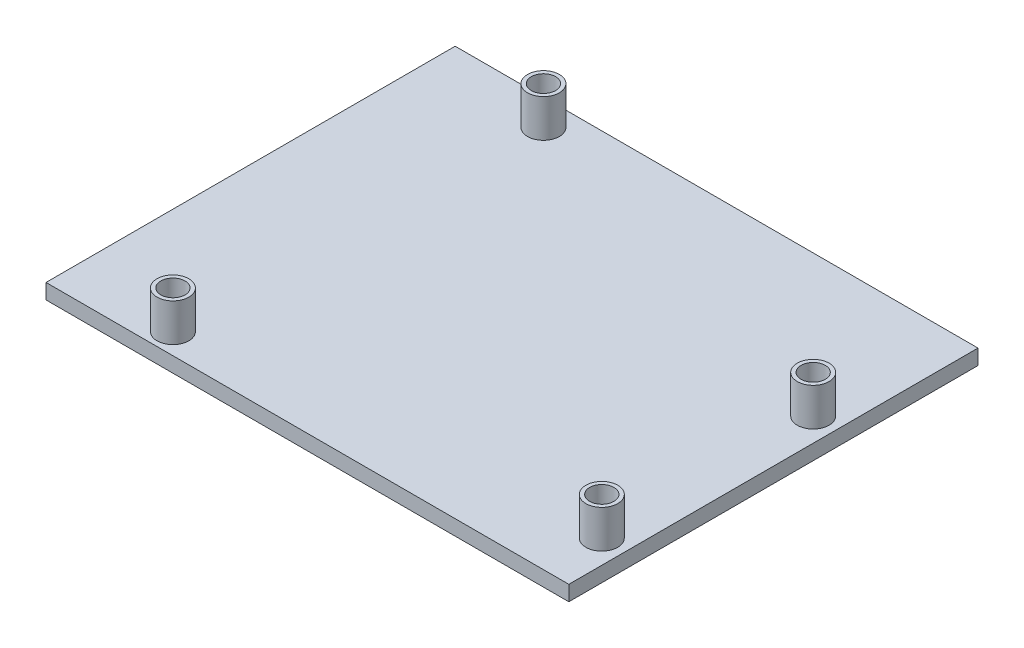
SolidWorks part; units mm, degrees
ref_plane "Front" through (0, 0, 0) normal (0, 0, 1) x (1, 0, 0)
ref_plane "Top" through (0, 0, 0) normal (0, 1, 0) x (1, 0, 0)
ref_plane "Right" through (0, 0, 0) normal (1, 0, 0) x (0, 0, -1)
sketch "Sketch1" plane through (0, 0, 0) normal (0, 1, 0) x (1, 0, 0)
  line L1 (-34.5, -27) -> (34.5, -27)
  line L2 (-34.5, -27) -> (-34.5, 27)
  line L3 (-34.5, 27) -> (34.5, 27)
  line L4 (34.5, -27) -> (34.5, 27)
  line L5 (-34.5, -27) -> (34.5, 27) construction
  line L6 (-34.5, 27) -> (34.5, -27) construction
  point P0 (0, 0)
  dimension "D1" = 69
  dimension "D2" = 54
extrude "Boss-Extrude1" add sketch "Sketch1" along normal blind 2
sketch "Sketch2" plane through (0, 2, 0) normal (0, 1, 0) x (1, 0, 0)
  line L0 (-34.5, -27) -> (34.5, -27) construction
  line L1 (-34.5, 27) -> (-34.5, -27) construction
  circle A0 centre (-20.5, -24.25) radius 1.6
  circle A1 centre (31.4, -19.55) radius 1.6
  circle A2 centre (31.4, 8.35) radius 1.6
  circle A3 centre (-19.4, 23.55) radius 1.6
  circle A4 centre (-19.4, 23.55) radius 2.1
  circle A5 centre (31.4, 8.35) radius 2.1
  circle A6 centre (31.4, -19.55) radius 2.1
  circle A7 centre (-20.5, -24.25) radius 2.1
  dimension "D1" = 3.2
  dimension "D2" = 14
  dimension "D3" = 7.45
  dimension "D7" = 15.1
  dimension "D8" = 50.55
  dimension "D9" = 4.2
  dimension "2.75" = 2.75
  dimension "D4" = 65.9
  dimension "D5" = 65.9
  dimension "D6" = 35.35
extrude "Boss-Extrude2" add sketch "Sketch2" along normal blind 5
